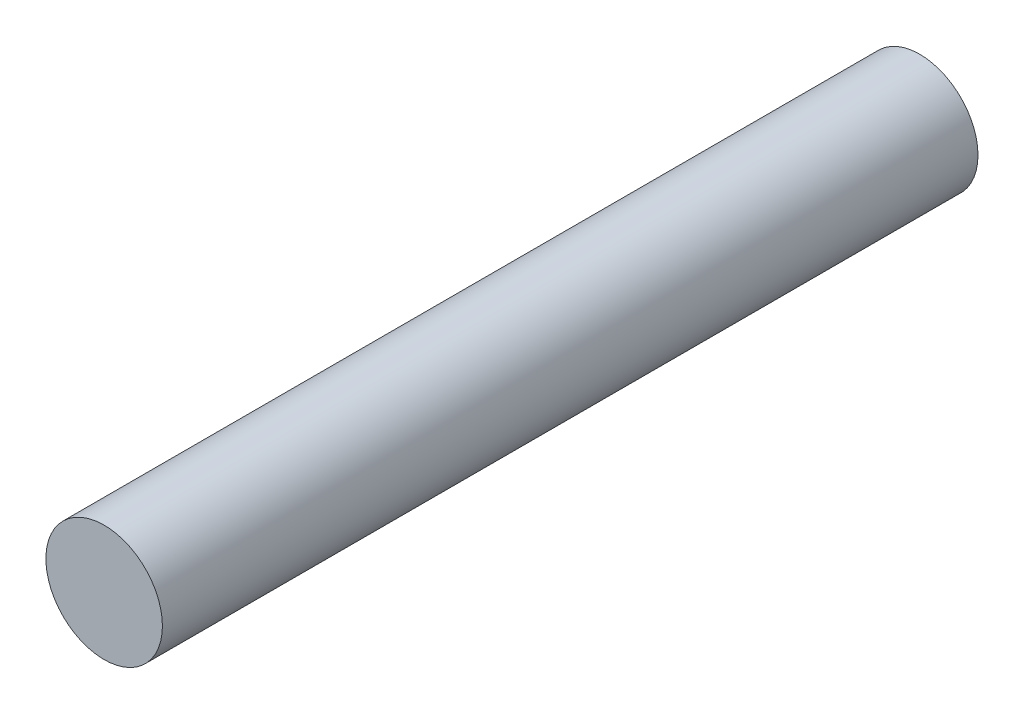
SolidWorks part; units mm, degrees
material "2024 Alloy"
ref_plane "Front Plane" through (0, 0, 0) normal (0, 0, 1) x (1, 0, 0)
ref_plane "Top Plane" through (0, 0, 0) normal (0, 1, 0) x (1, 0, 0)
ref_plane "Right Plane" through (0, 0, 0) normal (1, 0, 0) x (0, 0, -1)
sketch "Sketch1" plane through (0, 0, 0) normal (0, 0, 1) x (1, 0, 0)
  circle A0 centre (0, 0) radius 4
  dimension "D1" = 8
extrude "Boss-Extrude1" add sketch "Sketch1" along normal blind 56
